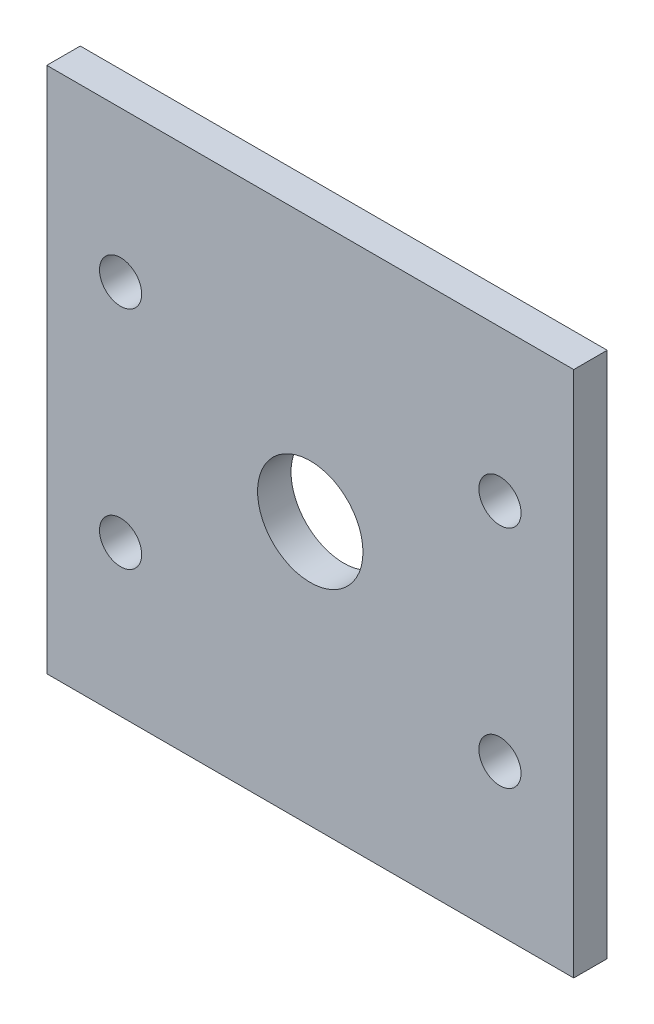
SolidWorks part; units mm, degrees
ref_plane "Plan de face" through (0, 0, 0) normal (0, 0, 1) x (1, 0, 0)
ref_plane "Plan de dessus" through (0, 0, 0) normal (0, 1, 0) x (1, 0, 0)
ref_plane "Plan de droite" through (0, 0, 0) normal (1, 0, 0) x (0, 0, -1)
sketch "Esquisse1" plane through (0, 0, 0) normal (0, 0, 1) x (1, 0, 0)
  line L1 (-12.5, -12.5) -> (12.5, -12.5)
  line L2 (-12.5, -12.5) -> (-12.5, 12.5)
  line L3 (-12.5, 12.5) -> (12.5, 12.5)
  line L4 (12.5, -12.5) -> (12.5, 12.5)
  line L5 (-12.5, -12.5) -> (12.5, 12.5) construction
  line L6 (-12.5, 12.5) -> (12.5, -12.5) construction
  circle A0 centre (0, 0) radius 2.5
  circle A1 centre (-9, 5.35) radius 1
  circle A2 centre (9, 5.35) radius 1
  circle A3 centre (-9, -5.35) radius 1
  circle A4 centre (9, -5.35) radius 1
  point P0 (0, 0)
  dimension "D3" = 7.15
  dimension "D5" = 3.5
  dimension "D6" = 7.15
  dimension "D1" = 25
  dimension "D2" = 25
  dimension "D4" = 3.5
extrude "Boss.-Extru.1" add sketch "Esquisse1" along normal blind 1.5875
